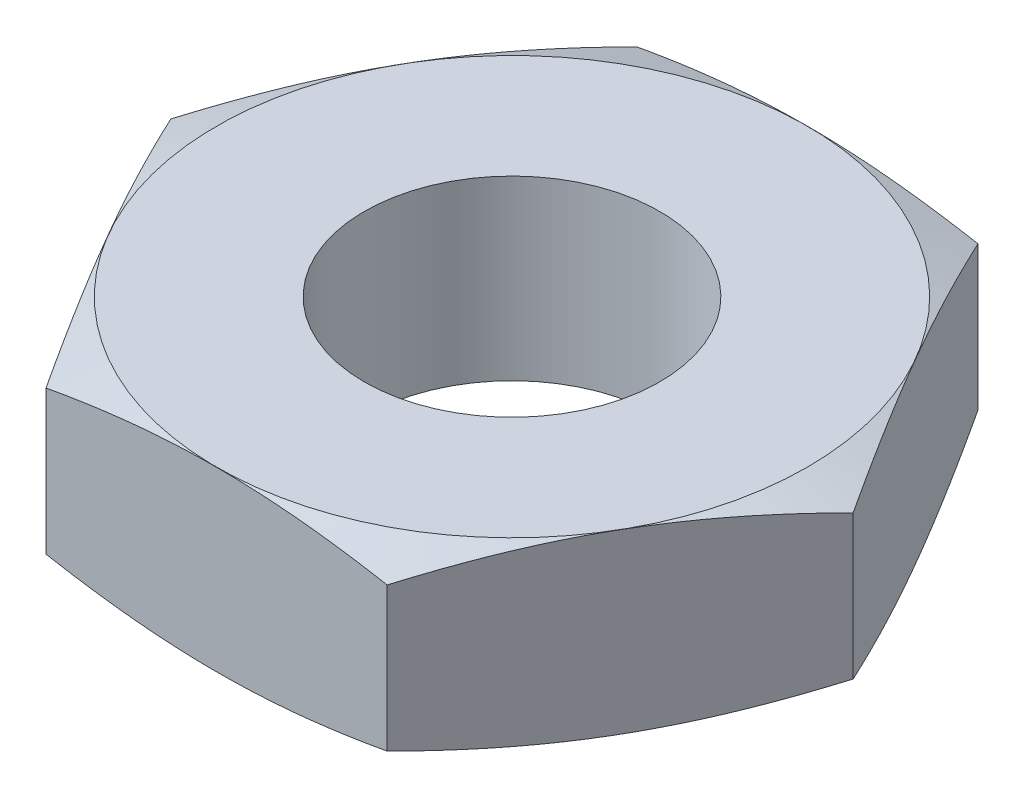
SolidWorks part; units mm, degrees
material "AISI 304"
ref_plane "前视基准面" through (0, 0, 0) normal (0, 0, 1) x (1, 0, 0)
ref_plane "上视基准面" through (0, 0, 0) normal (0, 1, 0) x (1, 0, 0)
ref_plane "右视基准面" through (0, 0, 0) normal (1, 0, 0) x (0, 0, -1)
sketch "Sketch2" plane through (0, 0, 0) normal (0, 1, 0) x (1, 0, 0)
  line L1 (2.3094, 0) -> (1.1547, 2)
  line L2 (1.1547, 2) -> (-1.1547, 2)
  line L3 (-1.1547, 2) -> (-2.3094, 0)
  line L4 (-2.3094, 0) -> (-1.1547, -2)
  line L5 (-1.1547, -2) -> (1.1547, -2)
  line L6 (1.1547, -2) -> (2.3094, 0)
  circle A0 centre (0, 0) radius 2 construction
  circle A1 centre (0, 0) radius 1
  dimension "公称直径" = 2
  dimension "对边距离" = 4
extrude "Boss-Extrude1" add sketch "Sketch2" along normal mid plane 1.2
sketch "Sketch3" plane through (0, 0, 0) normal (0, 0, 1) x (1, 0, 0)
  line L0 (0, 0) -> (-2.3094, 0) construction
  line L1 (-2.3094, 0.6) -> (-2.3094, -0.6) construction
  line L2 (-2.3094, 0.6) -> (-1.9994, 0.6)
  line L3 (-2.3094, 0.6) -> (-1.1547, 0.6) construction
  line L4 (-1.9994, 0.6) -> (-2.3094, 0.4872)
  line L5 (-2.3094, 0.4872) -> (-2.3094, 0.6)
  line L6 (0, 0) -> (0, 0.6) construction
  line L7 (-1.1547, 0.6) -> (1.1547, 0.6) construction
  line L8 (-1.9994, -0.6) -> (-2.3094, -0.4872)
  line L9 (-2.3094, -0.4872) -> (-2.3094, -0.6)
  line L10 (-2.3094, -0.6) -> (-1.9994, -0.6)
  dimension "切除角" = 20
  dimension "切除距离" = 0.31
revolve "Cut-Revolve1" cut sketch "Sketch3" angle 360 about L6
other "冻结***"
